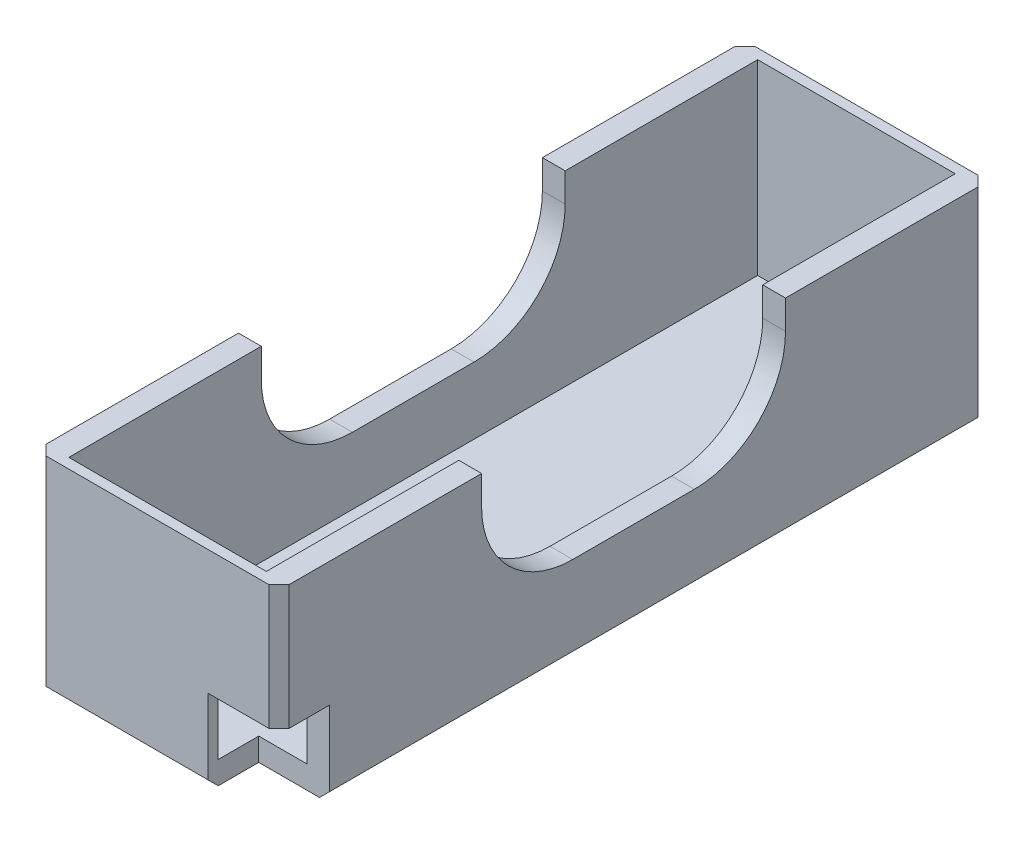
SolidWorks part; units mm, degrees
ref_plane "Front Plane" through (0, 0, 0) normal (0, 0, 1) x (1, 0, 0)
ref_plane "Top Plane" through (0, 0, 0) normal (0, 1, 0) x (1, 0, 0)
ref_plane "Right Plane" through (0, 0, 0) normal (1, 0, 0) x (0, 0, -1)
sketch "Sketch1" plane through (0, 0, 0) normal (0, 1, 0) x (1, 0, 0)
  line L1 (12, -35) -> (-12, -35)
  line L2 (12, -35) -> (12, 35)
  line L3 (12, 35) -> (-12, 35)
  line L4 (-12, -35) -> (-12, 35)
  line L5 (12, -35) -> (-12, 35) construction
  line L6 (12, 35) -> (-12, -35) construction
  point P0 (0, 0)
  dimension "D1" = 24
  dimension "D2" = 70
extrude "Boss-Extrude1" add sketch "Sketch1" along normal blind 20.7
sketch "Sketch2" plane through (0, 20.7, 0) normal (0, 1, 0) x (1, 0, 0)
  line L0 (12, 35) -> (-12, 35) construction
  line L1 (9.75, -34) -> (-9.75, -34)
  line L2 (9.75, -34) -> (9.75, 34)
  line L3 (9.75, 34) -> (-9.75, 34)
  line L4 (-9.75, -34) -> (-9.75, 34)
  line L5 (9.75, -34) -> (-9.75, 34) construction
  line L6 (9.75, 34) -> (-9.75, -34) construction
  line L7 (-12, 35) -> (-12, -35) construction
  point P0 (0, 0)
  dimension "D1" = 1
  dimension "D2" = 2.25
extrude "Cut-Extrude1" cut sketch "Sketch2" against normal offset from surface (18.45 mm away) 2.25 up to face at (0, 0, 0)
sketch "Sketch4" plane through (-12, 0, 0) normal (-1, 0, 0) x (0, 0, 1)
  line L0 (-35, 20.7) -> (-35, 0) construction
  line L1 (15, 8.85) -> (-15, 8.85)
  line L2 (15, 8.85) -> (15, 20.7)
  line L3 (15, 20.7) -> (-15, 20.7)
  line L4 (-15, 8.85) -> (-15, 20.7)
  line L5 (15, 8.85) -> (-15, 20.7) construction
  line L6 (15, 20.7) -> (-15, 8.85) construction
  line L7 (35, 20.7) -> (35, 0) construction
  line L8 (-35, 20.7) -> (35, 20.7) construction
  line L9 (-35, 0) -> (35, 0) construction
  point P0 (0, 14.775)
  dimension "D1" = 20
  dimension "D2" = 20
  dimension "D3" = 8.85
extrude "Cut-Extrude2" cut sketch "Sketch4" against normal through all both and the other way through all
fillet "Fillet1" radius 9 4 edges at (-10.875, 8.85, 15) (10.875, 8.85, 15) (-10.875, 8.85, -15) (10.875, 8.85, -15)
sketch "Sketch5" plane through (0, 0, 35) normal (0, 0, 1) x (1, 0, 0)
  line L0 (12, 20.7) -> (12, 0) construction
  line L1 (12, 0) -> (5, 0)
  line L2 (12, 0) -> (12, 8.41)
  line L3 (12, 8.41) -> (5, 8.41)
  line L4 (5, 0) -> (5, 8.41)
  line L5 (12, 0) -> (5, 8.41) construction
  line L6 (12, 8.41) -> (5, 0) construction
  line L7 (-12, 0) -> (12, 0) construction
  line L8 (-12, 20.7) -> (-12, 0) construction
  line L9 (-12, 20.7) -> (12, 20.7) construction
  point P0 (8.5, 4.205)
  dimension "D1" = 17
  dimension "D2" = 12.29
extrude "Cut-Extrude3" cut sketch "Sketch5" against normal blind 5
chamfer "Chamfer1" distance 1 angle 45 8 edges at (12, 14.555, 35) (12, 0, -2.5) (12, 10.35, -35) (0, 0, -35) (-12, 10.35, -35) (-12, 0, 0) (-3.5, 0, 35) (-12, 10.35, 35)
